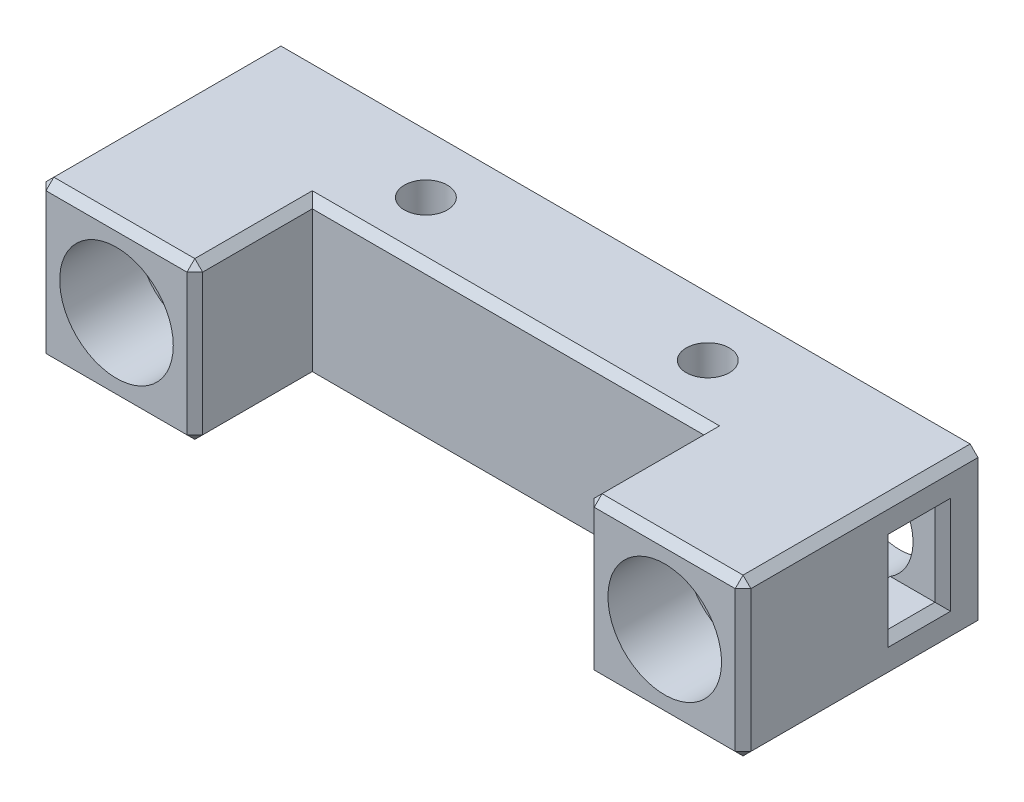
SolidWorks part; units mm, degrees
ref_plane "Front Plane" through (0, 0, 0) normal (0, 0, 1) x (1, 0, 0)
ref_plane "Top Plane" through (0, 0, 0) normal (0, 1, 0) x (1, 0, 0)
ref_plane "Right Plane" through (0, 0, 0) normal (1, 0, 0) x (0, 0, -1)
sketch "Sketch1" plane through (0, 0, 0) normal (0, 1, 0) x (1, 0, 0)
  line L0 (-45, 15) -> (45, 15)
  line L2 (-25, -15) -> (-45, -15)
  line L3 (-45, -15) -> (-45, -5)
  line L4 (-45, -5) -> (-45, 15)
  line L5 (-25, 0) -> (-25, -15)
  line L7 (25, 0) -> (-25, 0)
  line L8 (0, -1000) -> (0, 49000) construction
  line L9 (25, 0) -> (25, -15)
  line L10 (45, -5) -> (45, 15)
  line L11 (45, -15) -> (45, -5)
  line L12 (25, -15) -> (45, -15)
  point P13 (0, 0)
  point P18 (0, 15)
  dimension "D1" = 15
  dimension "D2" = 50
  dimension "D3" = 20
  dimension "D4" = 10
  dimension "D6" = 20
extrude "Body" add sketch "Sketch1" along normal mid plane 20
sketch "Sketch2" plane through (0, 0, 15) normal (0, 0, 1) x (1, 0, 0)
  line L1 (-25, 10) -> (-25, -10) construction
  circle A0 centre (-35, 0) radius 7.25
  dimension "D1" = 14.5
  dimension "D2" = 10
extrude "Spring_Hole" cut sketch "Sketch2" against normal blind 10
sketch "Sketch3" plane through (0, 0, 5) normal (0, 0, 1) x (1, 0, 0)
  circle A0 centre (-35, 0) radius 3.25
  dimension "D1" = 6.5
extrude "Shaft_Hole" cut sketch "Sketch3" against normal through all and the other way through all
sketch "Sketch4" plane through (0, 10, 0) normal (0, 1, 0) x (1, 0, 0)
  circle A0 centre (-18, 7.5) radius 2.75
  dimension "D1" = 5.5
  dimension "D2" = 18
  dimension "D3" = 7.5
extrude "Fixation_Hole" cut sketch "Sketch4" along normal through all from surface at -20 starting at face at (0, -10, 3.75)
sketch "Sketch6" plane through (-45, 0, 0) normal (-1, 0, 0) x (0, 0, 1)
  line L1 (-10.5, -5.25) -> (-4.5, -5.25)
  line L2 (-10.5, -5.25) -> (-10.5, 5.25)
  line L3 (-10.5, 5.25) -> (-4.5, 5.25)
  line L4 (-4.5, -5.25) -> (-4.5, 5.25)
  line L5 (-10.5, -5.25) -> (-4.5, 5.25) construction
  line L6 (-10.5, 5.25) -> (-4.5, -5.25) construction
  point P0 (-7.5, 0)
  dimension "D1" = 10.5
  dimension "D2" = 6
  dimension "D3" = 7.5
extrude "Nut_Hole" cut sketch "Sketch6" against normal blind 20
mirror "Mirror1" about plane through (0, 0, 0) normal (1, 0, 0) of "Nut_Hole", "Shaft_Hole", "Fixation_Hole", "Spring_Hole"
sketch "Sketch7" plane through (0, 0, -15) normal (0, 0, -1) x (-1, 0, 0)
  line L0 (0, -1000) -> (0, 49000) construction
  circle A0 centre (-10, 0) radius 3.2
  circle A1 centre (10, 0) radius 3.2
  dimension "D1" = 6.4
  dimension "D2" = 10
extrude "Inserts_Top" cut sketch "Sketch7" against normal blind 9.5
sketch "Sketch8" plane through (0, -10, 0) normal (0, -1, 0) x (1, 0, 0)
  circle A0 centre (-18, -7.5) radius 4.5
  circle A1 centre (18, -7.5) radius 4.5
  dimension "D1" = 9
extrude "M5_Screw_Place" cut sketch "Sketch8" against normal blind 5
sketch "Sketch9" plane through (0, 0, -15) normal (0, 0, -1) x (-1, 0, 0)
  circle A0 centre (-35, 0) radius 6.2
  dimension "D1" = 12.4
extrude "LinearBearingPlace" cut sketch "Sketch9" against normal blind 19
mirror "Mirror2" about plane through (0, 0, 0) normal (1, 0, 0) of "LinearBearingPlace"
chamfer "Chamfer1" distance 1 angle 45 18 edges at (-25, -10, 7.5) (-45, -10, 0) (-45, 10, 0) (0, -10, 0) (25, -10, 7.5) (45, -10, 0) (45, 10, 0) (35, 10, 15) (45, 0, 15) (35, -10, 15) (25, 0, 15) (25, 10, 7.5) (0, 10, 0) (-25, 10, 7.5) (-35, -10, 15) (-45, 0, 15) (-35, 10, 15) (-25, 0, 15)
chamfer "Chamfer2" distance 1 angle 45 8 edges at (-45, -5.25, -7.5) (-45, 0, -10.5) (-45, 5.25, -7.5) (-45, 0, -4.5) (45, 5.25, -7.5) (45, 0, -10.5) (45, 0, -4.5) (45, -5.25, -7.5)
